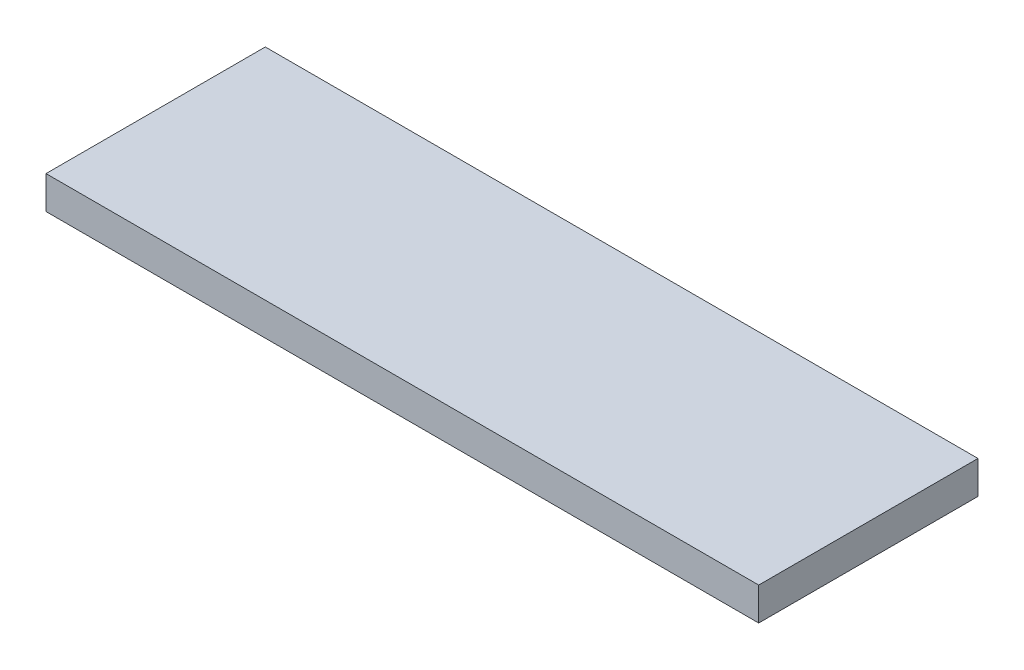
SolidWorks part; units mm, degrees
ref_plane "Front Plane" through (0, 0, 0) normal (0, 0, 1) x (1, 0, 0)
ref_plane "Top Plane" through (0, 0, 0) normal (0, 1, 0) x (1, 0, 0)
ref_plane "Right Plane" through (0, 0, 0) normal (1, 0, 0) x (0, 0, -1)
sketch "Sketch1" plane through (0, 0, 0) normal (0, 1, 0) x (1, 0, 0)
  line L1 (-65, 20) -> (65, 20)
  line L2 (-65, 20) -> (-65, -20)
  line L3 (-65, -20) -> (65, -20)
  line L4 (65, 20) -> (65, -20)
  line L5 (-65, 20) -> (65, -20) construction
  line L6 (-65, -20) -> (65, 20) construction
  point P0 (0, 0)
  dimension "D1" = 130
  dimension "D2" = 40
extrude "Boss-Extrude1" add sketch "Sketch1" along normal blind 6
sketch "Sketch2" plane through (0, 0, 0) normal (0, -1, 0) x (1, 0, 0)
  line L0 (-65, -20) -> (-65, 20) construction
  line L1 (-51.15, -6.15) -> (-38.85, -6.15)
  line L2 (-51.15, -6.15) -> (-51.15, 6.15)
  line L3 (-51.15, 6.15) -> (-38.85, 6.15)
  line L4 (-38.85, -6.15) -> (-38.85, 6.15)
  line L5 (-65, 20) -> (65, 20) construction
  dimension "D1" = 12.3
  dimension "D2" = 12.3
  dimension "D3" = 13.85
  dimension "D4" = 13.85
extrude "Boss-Extrude2" add sketch "Sketch2" along normal blind 10
pattern_linear "LPattern1" count 4 spacing 30 along (1, 0, 0) of "Boss-Extrude2"
chamfer "Chamfer1" distance 0.5 angle 45 16 edges at (45, -10, 6.15) (51.15, -10, 0) (45, -10, -6.15) (38.85, -10, 0) (15, -10, 6.15) (21.15, -10, 0) (15, -10, -6.15) (8.85, -10, 0) (-8.85, -10, 0) (-15, -10, -6.15) (-21.15, -10, 0) (-15, -10, 6.15) (-45, -10, 6.15) (-38.85, -10, 0) (-45, -10, -6.15) (-51.15, -10, 0)
